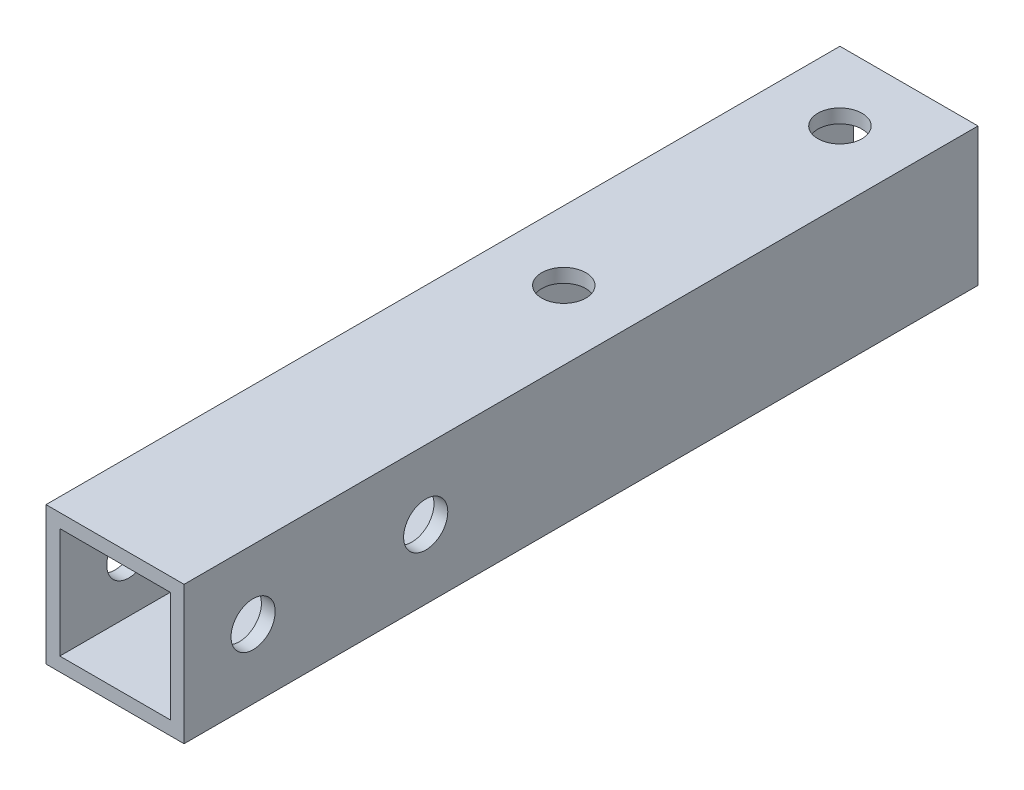
SolidWorks part; units mm, degrees
material "1060 合金"
ref_plane "正面" through (0, 0, 0) normal (0, 0, 1) x (1, 0, 0)
ref_plane "平面" through (0, 0, 0) normal (0, 1, 0) x (1, 0, 0)
ref_plane "右側面" through (0, 0, 0) normal (1, 0, 0) x (0, 0, -1)
sketch "ｽｹｯﾁ1" plane through (0, 0, 0) normal (0, 0, 1) x (1, 0, 0)
  line L1 (-5, -5) -> (5, -5)
  line L2 (-5, -5) -> (-5, 5)
  line L3 (-5, 5) -> (5, 5)
  line L4 (5, -5) -> (5, 5)
  line L5 (-5, -5) -> (5, 5) construction
  line L6 (-5, 5) -> (5, -5) construction
  point P0 (0, 0)
  dimension "D1" = 10
extrude "押し出し-薄板1" add sketch "ｽｹｯﾁ1" along normal blind 57.5 thin thin type one direction reverse wall 1
sketch "ｽｹｯﾁ2" plane through (0, 5, 0) normal (0, 1, 0) x (1, 0, 0)
  line L0 (0, 0) -> (0, -57.5) construction
  line L1 (5, -57.5) -> (-5, -57.5) construction
  line L2 (5, 0) -> (-5, 0) construction
  circle A1 centre (0, -5) radius 1.6
  circle A2 centre (0, -25) radius 1.6
  dimension "D1" = 3.2
  dimension "D2" = 20
  dimension "D3" = 5
extrude "ｶｯﾄ - 押し出し1" cut sketch "ｽｹｯﾁ2" against normal through all
sketch "ｽｹｯﾁ4" plane through (5, 0, 0) normal (1, 0, 0) x (0, 0, -1)
  line L0 (-57.5, 0) -> (0, 0)
  line L1 (-57.5, -5) -> (-57.5, 5) construction
  circle A0 centre (-52.5, 0) radius 1.6
  circle A1 centre (-40, 0) radius 1.6
  dimension "D1" = 3.2
  dimension "D2" = 5
  dimension "D3" = 12.5
extrude "ｶｯﾄ - 押し出し2" cut sketch "ｽｹｯﾁ4" against normal blind 10 contours L0 A1 | L0 A1 | L0 A0 | L0 A0
